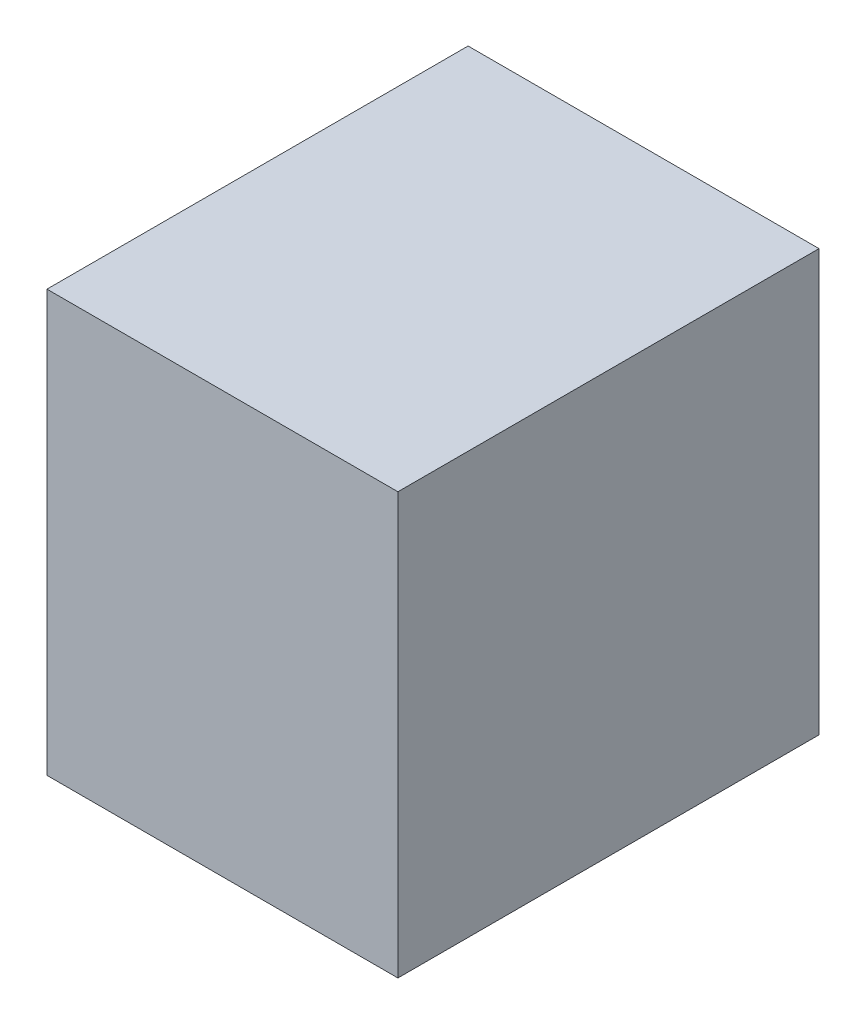
SolidWorks part; units mm, degrees
ref_plane "Front Plane" through (0, 0, 0) normal (0, 0, 1) x (1, 0, 0)
ref_plane "Top Plane" through (0, 0, 0) normal (0, 1, 0) x (1, 0, 0)
ref_plane "Right Plane" through (0, 0, 0) normal (1, 0, 0) x (0, 0, -1)
other "Configuration Table"
sketch "Sketch1" plane through (0, 0, 0) normal (0, 0, 1) x (1, 0, 0)
  line L1 (125, 640) -> (175, 640)
  line L2 (125, 640) -> (125, 700)
  line L3 (125, 700) -> (175, 700)
  line L4 (175, 640) -> (175, 700)
extrude "PACK_flap_servo_25kgcm_1_1" add sketch "Sketch1" against normal blind 60 from offset 170 separate body
